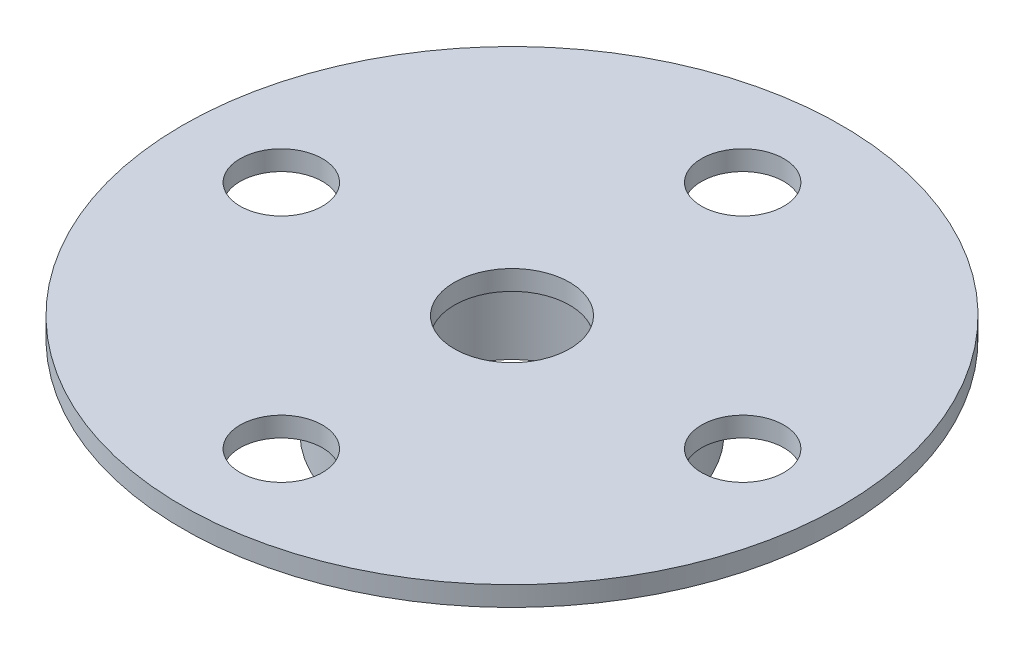
SolidWorks part; units mm, degrees
ref_plane "Front Plane" through (0, 0, 0) normal (0, 0, 1) x (1, 0, 0)
ref_plane "Top Plane" through (0, 0, 0) normal (0, 1, 0) x (1, 0, 0)
ref_plane "Right Plane" through (0, 0, 0) normal (1, 0, 0) x (0, 0, -1)
sketch "Sketch2" plane through (0, 0, 0) normal (0, 0, 1) x (1, 0, 0)
  line L0 (1.75, 0) -> (10, 0)
  line L1 (10, 0) -> (10, -0.6)
  line L2 (10, -0.6) -> (4.55, -0.6)
  line L3 (4.55, -0.6) -> (4.55, -3.1)
  line L4 (4.55, -3.1) -> (2.75, -3.1)
  line L5 (2.75, -3.1) -> (2.75, -0.6)
  line L6 (2.75, -0.6) -> (1.75, -0.6)
  line L7 (1.75, 0) -> (1.75, -0.6)
  line L8 (0, 0) -> (0, -2.9445) construction
  point P10 (3.8598, -2.302)
  dimension "D1" = 4.55
  dimension "D2" = 10
  dimension "D3" = 1.75
  dimension "D4" = 0.6
  dimension "D5" = 2.75
  dimension "D6" = 2.5
revolve "Revolve1" add sketch "Sketch2" angle 360 about L8
sketch "Sketch3" plane through (0, 0, 0) normal (0, 1, 0) x (1, 0, 0)
  line L0 (-4.8424, 5.75) -> (4.2514, 5.75) construction
  line L1 (-4.658, 8.25) -> (5.6513, 8.25) construction
  line L2 (-4.658, -1.75) -> (4.7887, -1.75) construction
  line L3 (-4.4797, 1.75) -> (1.5524, 1.75) construction
  line L4 (0, 0) -> (0, 7) construction
  circle A0 centre (0, 7) radius 1.25
  circle A1 centre (0, 0) radius 10 construction
  circle A2 centre (0, 0) radius 1.75 construction
  circle A3 centre (7, 0) radius 1.25
  circle A4 centre (0, -7) radius 1.25
  circle A5 centre (-7, 0) radius 1.25
  point P15 (-1.2972, 0.1212)
  dimension "D1" = 2.5
  dimension "D2" = 7
  dimension "D3" = 4
  dimension "D4" = 7
extrude "Cut-Extrude1" cut sketch "Sketch3" against normal through all
